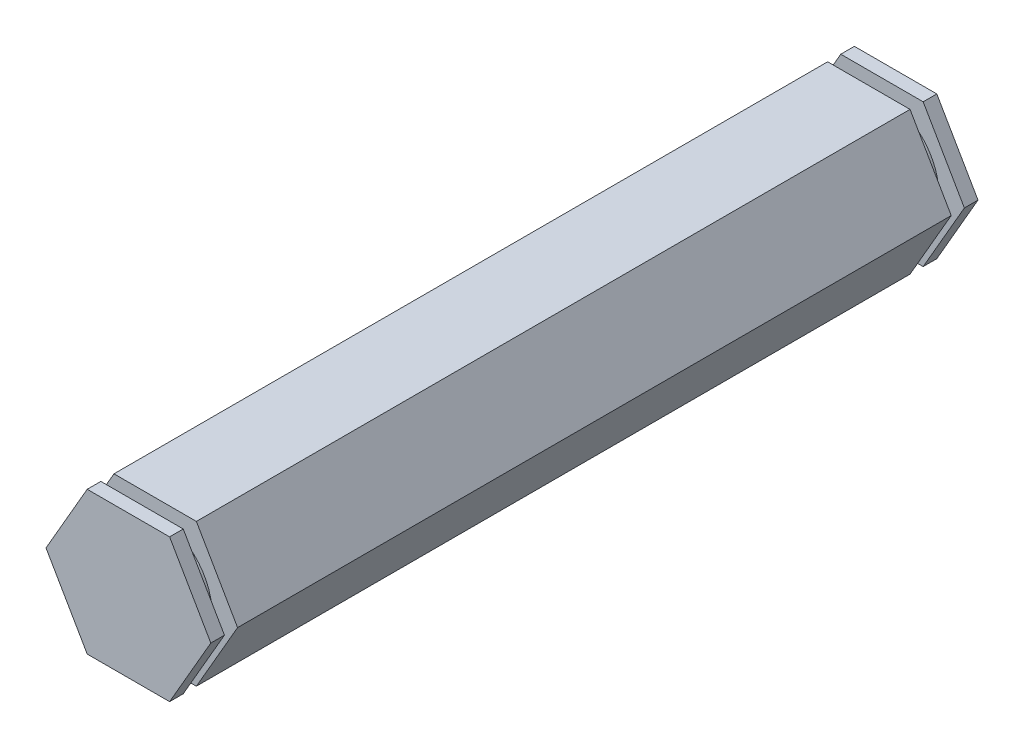
SolidWorks part; units mm, degrees
material "7075-T6 (SN)"
ref_plane "Front Plane" through (0, 0, 0) normal (0, 0, 1) x (1, 0, 0)
ref_plane "Top Plane" through (0, 0, 0) normal (0, 1, 0) x (1, 0, 0)
ref_plane "Right Plane" through (0, 0, 0) normal (1, 0, 0) x (0, 0, -1)
sketch "Sketch1" plane through (0, 0, 0) normal (0, 0, 1) x (1, 0, 0)
  line L1 (-3.6662, 6.35) -> (-7.3323, 0)
  line L2 (-7.3323, 0) -> (-3.6662, -6.35)
  line L3 (-3.6662, -6.35) -> (3.6662, -6.35)
  line L4 (3.6662, -6.35) -> (7.3323, 0)
  line L5 (7.3323, 0) -> (3.6662, 6.35)
  line L6 (3.6662, 6.35) -> (-3.6662, 6.35)
  circle A0 centre (0, 0) radius 6.35 construction
  dimension "D1" = 12.7
extrude "Boss-Extrude1" add sketch "Sketch1" along normal mid plane 68.2625
sketch "Sketch2" plane through (0, 0, 0) normal (1, 0, 0) x (0, 0, -1)
  line L0 (0, 0) -> (-31.75, 0) construction
  line L1 (-34.1313, 0) -> (34.1313, 0) construction
  line L2 (-31.75, 0) -> (-31.75, 5.0546) construction
  line L4 (-32.9184, 5.0546) -> (-31.75, 5.0546)
  line L5 (-32.9184, 5.0546) -> (-32.9184, 9.4701)
  line L6 (-32.9184, 9.4701) -> (-31.75, 9.4701)
  line L7 (-31.75, 5.0546) -> (-31.75, 9.4701)
  dimension "D1" = 1.1684
  dimension "D2" = 5.0546
  dimension "D3" = 31.75
revolve "Cut-Revolve1" cut sketch "Sketch2" angle 360 about L0
mirror "Mirror1" about plane through (0, 0, 0) normal (0, 0, 1) of "Cut-Revolve1"
